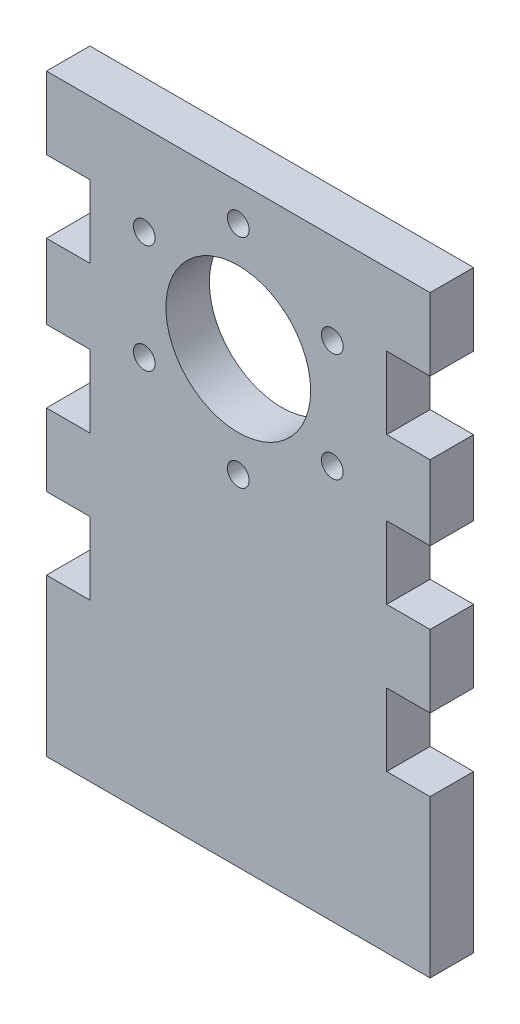
SolidWorks part; units mm, degrees
ref_plane "Alzado" through (0, 0, 0) normal (0, 0, 1) x (1, 0, 0)
ref_plane "Planta" through (0, 0, 0) normal (0, 1, 0) x (1, 0, 0)
ref_plane "Vista lateral" through (0, 0, 0) normal (1, 0, 0) x (0, 0, -1)
sketch "Sketch1" plane through (0, 0, 0) normal (0, 0, 1) x (1, 0, 0)
  line L0 (-13.25, 15.5) -> (-10.25, 15.5)
  line L1 (-13.25, 20.5) -> (13.25, 20.5)
  line L2 (-13.25, 20.5) -> (-13.25, 15.5)
  line L3 (-13.25, -20.5) -> (13.25, -20.5)
  line L4 (13.25, 20.5) -> (13.25, 15.5)
  line L5 (-13.25, 20.5) -> (13.25, -20.5) construction
  line L6 (-13.25, -20.5) -> (13.25, 20.5) construction
  line L7 (-10.25, 15.5) -> (-10.25, 10.5)
  line L8 (-10.25, 10.5) -> (-13.25, 10.5)
  line L9 (-13.25, 5.35) -> (-10.25, 5.35)
  line L10 (-10.25, 5.35) -> (-10.25, 0.35)
  line L11 (-10.25, 0.35) -> (-13.25, 0.35)
  line L12 (-13.25, -4.65) -> (-10.25, -4.65)
  line L13 (-10.25, -4.65) -> (-10.25, -9.65)
  line L14 (-10.25, -9.65) -> (-13.25, -9.65)
  line L15 (0, 20.5) -> (0, -20.5) construction
  line L16 (10.25, -9.65) -> (13.25, -9.65)
  line L17 (10.25, -4.65) -> (10.25, -9.65)
  line L18 (13.25, -4.65) -> (10.25, -4.65)
  line L19 (10.25, 0.35) -> (13.25, 0.35)
  line L20 (10.25, 5.35) -> (10.25, 0.35)
  line L21 (13.25, 5.35) -> (10.25, 5.35)
  line L22 (10.25, 10.5) -> (13.25, 10.5)
  line L23 (10.25, 15.5) -> (10.25, 10.5)
  line L24 (13.25, 15.5) -> (10.25, 15.5)
  line L25 (-13.25, 10.5) -> (-13.25, 5.35)
  line L26 (-13.25, 0.35) -> (-13.25, -4.65)
  line L27 (-13.25, -9.65) -> (-13.25, -20.5)
  line L28 (13.25, -9.65) -> (13.25, -20.5)
  line L29 (13.25, 0.35) -> (13.25, -4.65)
  line L30 (13.25, 10.5) -> (13.25, 5.35)
  line L31 (-6.4952, 14.25) -> (6.4952, 6.75) construction
  line L32 (6.4953, 14.2498) -> (-6.4953, 6.7502) construction
  circle A0 centre (0, 10.5) radius 5
  circle A1 centre (0, 10.5) radius 7.5 construction
  circle A2 centre (0, 18) radius 0.75
  circle A3 centre (6.4953, 14.2498) radius 0.75
  circle A4 centre (6.4952, 6.75) radius 0.75
  circle A5 centre (0, 3) radius 0.75
  circle A6 centre (-6.4953, 6.7502) radius 0.75
  circle A7 centre (-6.4952, 14.25) radius 0.75
  point P0 (0, 0)
  point P49 (0, 10.5)
  point P50 (0, 10.5)
  dimension "D8" = 10
  dimension "D10" = 15
  dimension "D11" = 1.5
  dimension "D1" = 26.5
  dimension "D2" = 41
  dimension "D3" = 3
  dimension "D4" = 5
  dimension "D5" = 5
  dimension "D6" = 5.15
  dimension "D7" = 5
  dimension "D9" = 10
  dimension "D12" = 60
  dimension "D13" = 59.998
extrude "Boss-Extrude1" add sketch "Sketch1" along normal blind 3
